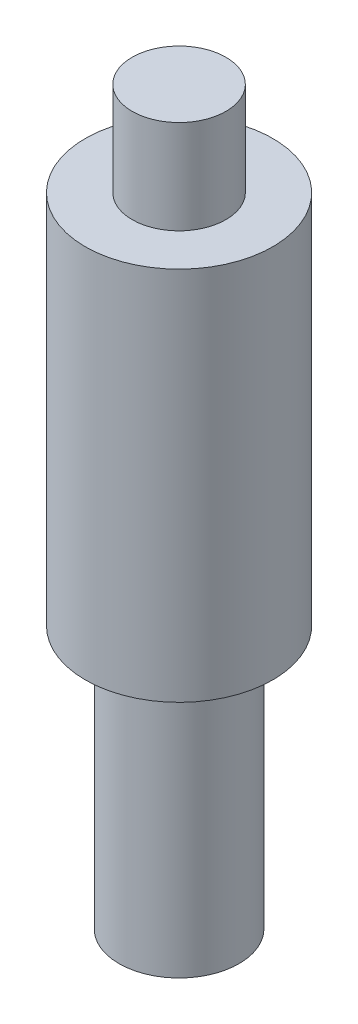
SolidWorks part; units mm, degrees
ref_plane "前视基准面" through (0, 0, 0) normal (0, 0, 1) x (1, 0, 0)
ref_plane "上视基准面" through (0, 0, 0) normal (0, 1, 0) x (1, 0, 0)
ref_plane "右视基准面" through (0, 0, 0) normal (1, 0, 0) x (0, 0, -1)
other "Configuration Table"
sketch "草图1" plane through (0, 0, 0) normal (0, 1, 0) x (1, 0, 0)
  circle A0 centre (0, 0) radius 1.6
  dimension "D1" = 3.2
extrude "凸台-拉伸1" add sketch "草图1" along normal blind 7 contours A0
sketch "草图2" plane through (0, 7, 0) normal (0, 1, 0) x (1, 0, 0)
  circle A0 centre (0, 0) radius 2.5
  dimension "D1" = 5
extrude "凸台-拉伸2" add sketch "草图2" along normal blind 10 contours A0
sketch "草图3" plane through (0, 17, 0) normal (0, 1, 0) x (1, 0, 0)
  circle A0 centre (0, 0) radius 1.25
  dimension "D1" = 2.5
extrude "凸台-拉伸3" add sketch "草图3" along normal blind 2.5
